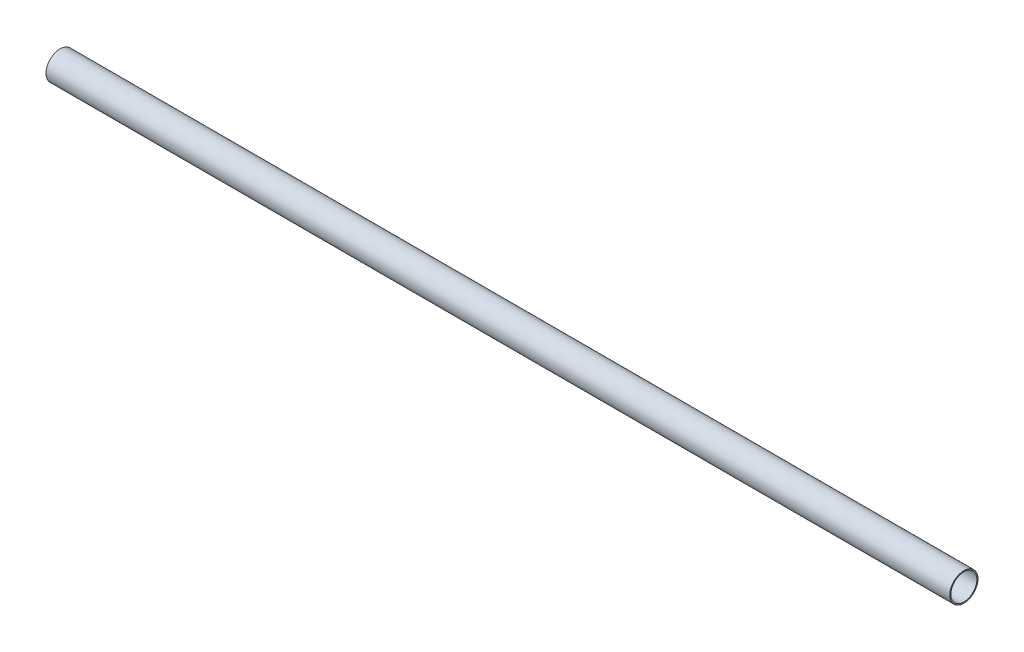
SolidWorks part; units mm, degrees
ref_plane "Front" through (0, 0, 0) normal (0, 0, 1) x (1, 0, 0)
ref_plane "Top" through (0, 0, 0) normal (0, 1, 0) x (1, 0, 0)
ref_plane "Right" through (0, 0, 0) normal (1, 0, 0) x (0, 0, -1)
sketch "Sketch1" plane through (0, 0, 0) normal (1, 0, 0) x (0, 0, -1)
  circle A0 centre (0, 0) radius 6.35
  circle A1 centre (0, 0) radius 5.842
  point P4 (6.35, 0)
  point P5 (5.842, 0)
  dimension "OD" = 12.7
  dimension "ID" = 11.684
  dimension "Wall" = 0.508
extrude "Extrude1" add sketch "Sketch1" along normal mid plane 914.4
sketch "Sketch4" plane through (-457.2, 0, 0) normal (-1, 0, 0) x (0, 0, 1)
  circle A1 centre (0, 0) radius 6.35
  circle A2 centre (0, 0) radius 6.35
  dimension "D1" = 0
sketch "Sketch5" plane through (-457.2, 0, 0) normal (-1, 0, 0) x (0, 0, 1)
  circle A0 centre (0, 0) radius 5.842 construction
  circle A1 centre (0, 0) radius 6.35 construction
  circle A2 centre (0, 0) radius 5.842
  circle A3 centre (0, 0) radius 6.35
extrude "Cut-Extrude1" cut sketch "Sketch5" against normal offset from surface (508 mm away) 406.4 up to face at (457.2, 0, -6.35)
